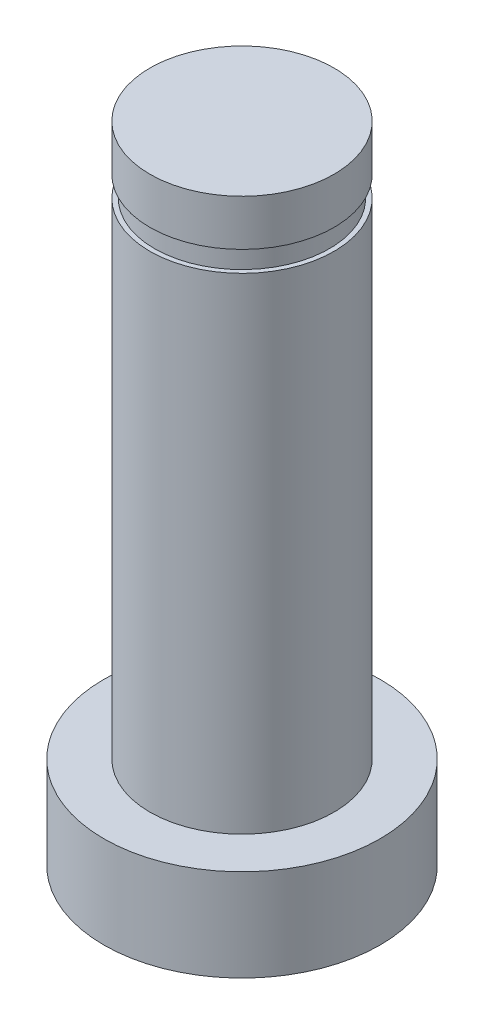
SolidWorks part; units mm, degrees
material "合金钢"
ref_plane "前视基准面" through (0, 0, 0) normal (0, 0, 1) x (1, 0, 0)
ref_plane "上视基准面" through (0, 0, 0) normal (0, 1, 0) x (1, 0, 0)
ref_plane "右视基准面" through (0, 0, 0) normal (1, 0, 0) x (0, 0, -1)
sketch "草图1" plane through (0, 0, 0) normal (0, 1, 0) x (1, 0, 0)
  circle A0 centre (0, 0) radius 6
  dimension "D1" = 12
extrude "凸台-拉伸1" add sketch "草图1" along normal blind 4
sketch "草图2" plane through (0, 4, 0) normal (0, 1, 0) x (1, 0, 0)
  circle A0 centre (0, 0) radius 4
  dimension "D1" = 8
extrude "凸台-拉伸2" add sketch "草图2" along normal blind 21.1
sketch "草图3" plane through (0, 25.1, 0) normal (0, 1, 0) x (1, 0, 0)
  circle A0 centre (0, 0) radius 3.8
  dimension "D1" = 7.6
extrude "凸台-拉伸3" add sketch "草图3" along normal blind 0.9
sketch "草图4" plane through (0, 26, 0) normal (0, 1, 0) x (1, 0, 0)
  circle A0 centre (0, 0) radius 4
extrude "凸台-拉伸4" add sketch "草图4" along normal blind 2
